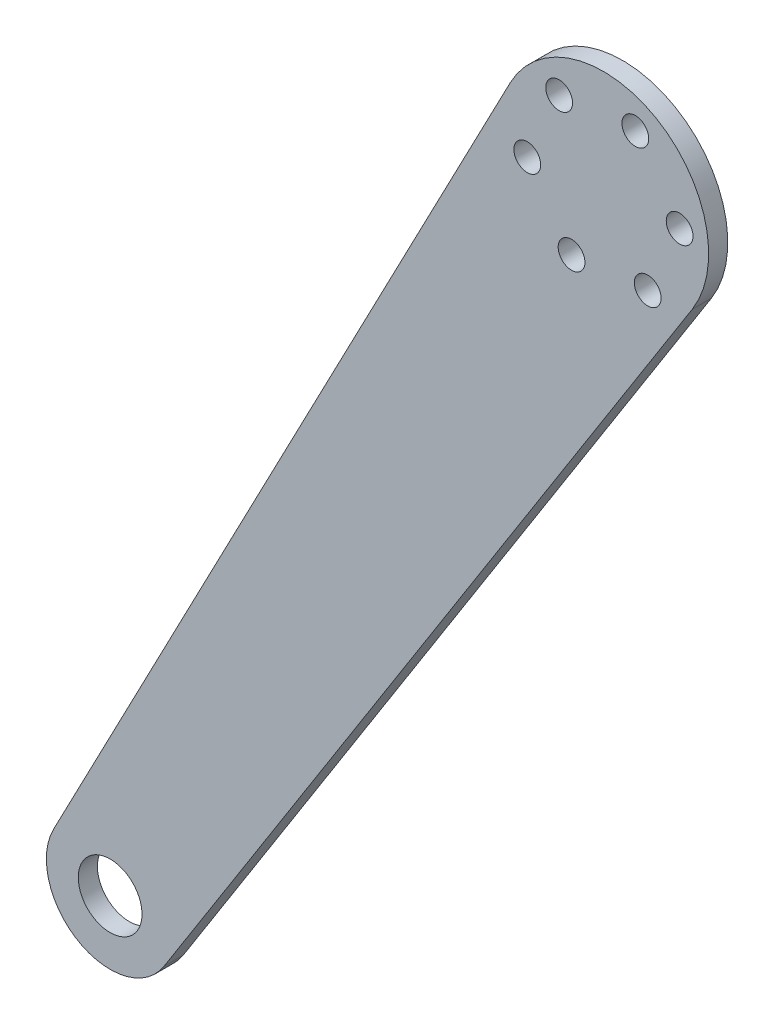
SolidWorks part; units mm, degrees
material "3240环氧板"
ref_plane "前视基准面" through (0, 0, 0) normal (0, 0, 1) x (1, 0, 0)
ref_plane "上视基准面" through (0, 0, 0) normal (0, 1, 0) x (1, 0, 0)
ref_plane "右视基准面" through (0, 0, 0) normal (1, 0, 0) x (0, 0, -1)
other "Configuration Table"
sketch "草图1" plane through (0, 0, 40.0567) normal (0, 0, -1) x (-1, 0, 0)
  line L0 (-2.9768, 49.5736) -> (74.3916, -84.5862) construction
  line L1 (83.2563, -79.9585) -> (11.6501, 57.2093)
  line L2 (-16.9117, 40.7381) -> (65.9461, -89.9411)
  line L3 (-12.7619, 56.52) -> (-2.9768, 49.5736) construction
  line L4 (-2.9768, 49.5736) -> (-4.1, 37.6263) construction
  line L5 (-2.9768, 49.5736) -> (7.9315, 54.5746) construction
  line L6 (-7.9777, 60.4819) -> (-2.9768, 49.5736) construction
  line L7 (-2.9768, 49.5736) -> (3.9696, 59.3587) construction
  line L8 (-2.9768, 49.5736) -> (8.9706, 48.4504) construction
  line L9 (-2.9768, 49.5736) -> (2.0242, 38.6653) construction
  line L10 (-2.9768, 49.5736) -> (-9.9231, 39.7885) construction
  line L11 (-14.9241, 50.6968) -> (-2.9768, 49.5736) construction
  arc A0 (11.6501, 57.2093) -> (-16.9117, 40.7381) centre (-2.9768, 49.5736) ccw
  arc A1 (65.9461, -89.9411) -> (83.2563, -79.9585) centre (74.3916, -84.5862) ccw
  circle A2 centre (74.3916, -84.5862) radius 5
  circle A9 centre (-14.9241, 50.6968) radius 2.1
  circle A10 centre (-7.9777, 60.4819) radius 2.1
  circle A11 centre (3.9696, 59.3587) radius 2.1
  circle A12 centre (8.9706, 48.4504) radius 2.1
  circle A13 centre (2.0242, 38.6653) radius 2.1
  circle A14 centre (-9.9231, 39.7885) radius 2.1
  circle A19 centre (-2.9768, 49.5736) radius 12 construction
  point P36 (-2.9768, 49.5736)
  dimension "D1" = 154.87
  dimension "D2" = 20
  dimension "D3" = 10
  dimension "D4" = 33
  dimension "D5" = 4.2
  dimension "D8" = 4.5158
  dimension "D9" = 120
  dimension "D10" = 120
extrude "凸台-拉伸1" add sketch "草图1" along normal blind 3
